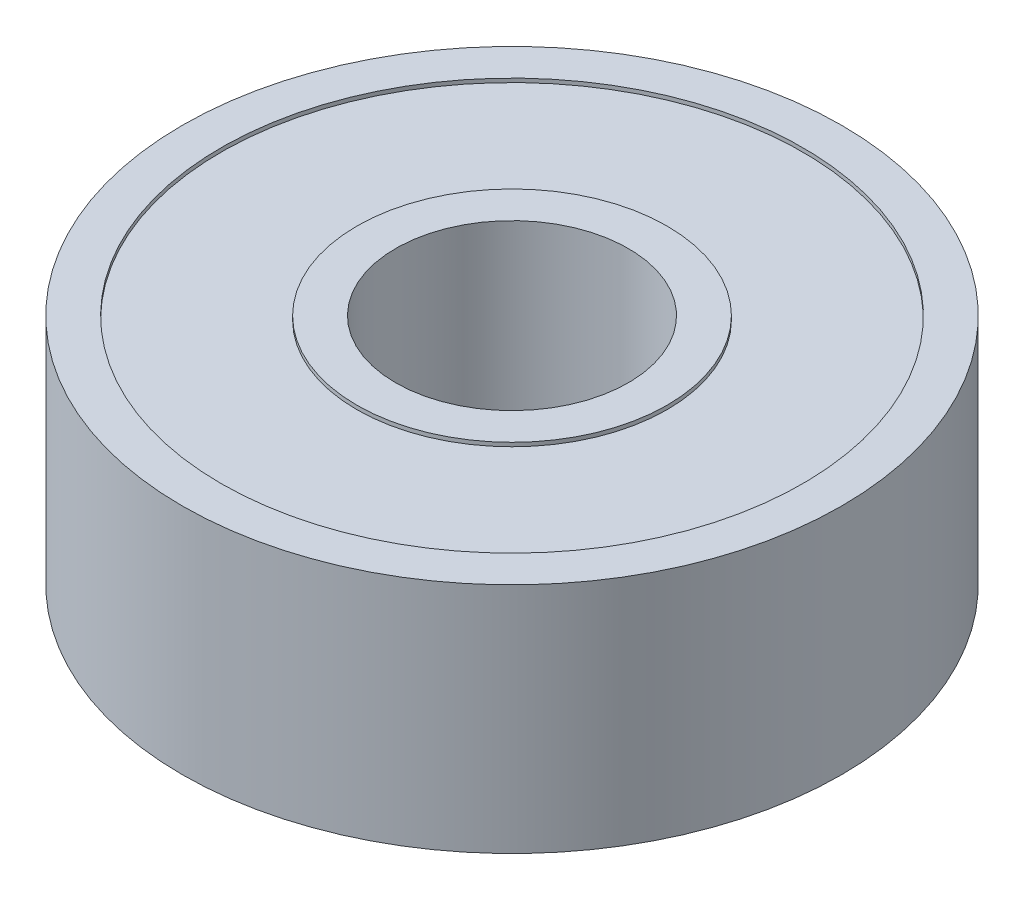
SolidWorks part; units mm, degrees
ref_plane "Front Plane" through (0, 0, 0) normal (0, 0, 1) x (1, 0, 0)
ref_plane "Top Plane" through (0, 0, 0) normal (0, 1, 0) x (1, 0, 0)
ref_plane "Right Plane" through (0, 0, 0) normal (1, 0, 0) x (0, 0, -1)
sketch "Sketch3" plane through (0, 0, 0) normal (0, 1, 0) x (1, 0, 0)
  circle A0 centre (0, 0) radius 3
  circle A1 centre (0, 0) radius 8.5
  dimension "D1" = 6
  dimension "D2" = 17
extrude "Boss-Extrude2" add sketch "Sketch3" along normal blind 6
sketch "Sketch4" plane through (0, 6, 0) normal (0, 1, 0) x (1, 0, 0)
  circle A2 centre (0, 0) radius 7.5
  circle A3 centre (0, 0) radius 7.5
  circle A5 centre (0, 0) radius 4
  circle A6 centre (0, 0) radius 4
  dimension "D1" = 1
  dimension "D2" = 1
extrude "Cut-Extrude2" cut sketch "Sketch4" against normal blind 0.1
ref_plane "Plane2" through (0, 3, 0) normal (0, 1, 0) x (1, 0, 0)
mirror "Mirror2" about plane through (0, 3, 0) normal (0, 1, 0) of "Cut-Extrude2"
